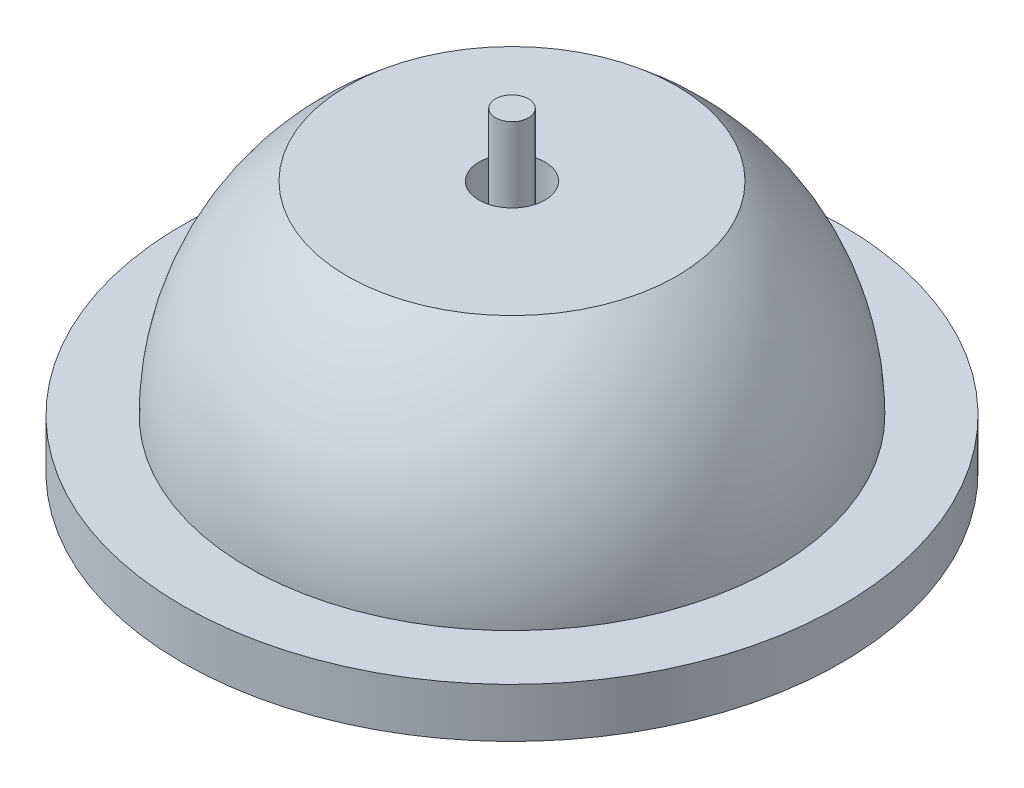
SolidWorks part; units mm, degrees
ref_plane "Front Plane" through (0, 0, 0) normal (0, 0, 1) x (1, 0, 0)
ref_plane "Top Plane" through (0, 0, 0) normal (0, 1, 0) x (1, 0, 0)
ref_plane "Right Plane" through (0, 0, 0) normal (1, 0, 0) x (0, 0, -1)
sketch "Sketch1" plane through (0, 0, 0) normal (0, 0, 1) x (1, 0, 0)
  line L0 (0, -54.4301) -> (0, 93.2078) construction
  line L1 (0, -64.8939) -> (0, 64.8939) construction
  line L2 (0, 0) -> (-100, 0)
  line L3 (-100, 0) -> (-100, 15)
  line L4 (-100, 15) -> (-80, 15)
  line L5 (-50, 76.5636) -> (0, 76.5636)
  line L6 (0, 76.5636) -> (0, 0)
  arc A0 (-80, 15) -> (-50, 76.5636) centre (-1.8321, 15) cw
revolve "Revolve1" add sketch "Sketch1" angle 360 about L0
sketch "Sketch5" plane through (0, 0, 0) normal (0, 0, 1) x (1, 0, 0)
  line L0 (0, -4.6123) -> (0, 80.659) construction
  line L1 (0, -64.8939) -> (0, 64.8939) construction
  line L2 (0, 80.659) -> (0, -4.6123)
  line L3 (0, -4.6123) -> (-10, -4.6123)
  line L4 (-10, -4.6123) -> (-10, 80.659)
  line L5 (-10, 80.659) -> (0, 80.659)
  dimension "D1" = 10
revolve "Cut-Revolve3" cut sketch "Sketch5" angle 360 about L0
ref_axis "Axis3" through (0, -28.2037, 0) along (0, 1, 0)
sketch "Sketch6" plane through (0, 0, 0) normal (0, 0, 1) x (1, 0, 0)
  line L0 (0, 95.6847) -> (-4.9974, 95.6847)
  line L1 (0, -64.8939) -> (0, 64.8939) construction
  line L2 (0, -28.2037) -> (0, 101.5841) construction
  line L3 (-4.9974, 95.6847) -> (-4.9974, -4.1791)
  line L4 (-4.9974, -4.1791) -> (0, -4.1791)
  line L5 (0, -4.1791) -> (0, 95.6847)
  dimension "D1" = 99.8638
  dimension "D2" = 99.8638
revolve "Revolve5" add sketch "Sketch6" angle 360 about L5
sketch "Sketch7" plane through (0, 0, 0) normal (0, 0, 1) x (1, 0, 0)
  line L0 (0, -4.1791) -> (-15.6433, -4.1791)
  line L1 (-4.9974, -4.1791) -> (4.9974, -4.1791) construction
  line L2 (0, -19.7299) -> (0, -4.1791)
  line L3 (-15.6433, -4.1791) -> (0, -19.7299) construction
  line L4 (0, -19.7299) -> (-13.0661, -24.8785) construction
  line L5 (-13.0661, -24.8785) -> (0, -19.7299) construction
  spline S0 degree 3 poles (-15.6433, -4.1791) (0, -19.7299) (-13.0661, -24.8785) (0, -19.7299) knots 0 0 0 0 1 1 1 1
  point P7 (0, 0)
  point P9 (0, -18.9922)
revolve "Revolve7" add sketch "Sketch7" angle 360 about axis through (0, -28.2037, 0) along (0, 1, 0)
sketch "Sketch8" plane through (0, 0, 0) normal (0, 0, 1) x (1, 0, 0)
  line L0 (72.1009, 49.242) -> (51.4251, 39.1667)
  line L1 (51.4251, 39.1667) -> (51.4251, 34.1667)
  line L2 (51.4251, 34.1667) -> (26.2096, 34.1667)
  line L3 (26.2096, 34.1667) -> (26.2096, 31.0304)
  line L4 (26.2096, 31.0304) -> (51.4251, 31.0304)
  line L5 (51.4251, 31.0304) -> (51.4251, 34.1667)
  line L6 (51.4251, 31.0304) -> (53.3272, 29.4754)
  line L7 (53.3272, 29.4754) -> (51.4251, 28.5485)
  line L8 (51.4251, 28.5485) -> (53.3272, 26.9935)
  line L9 (53.3272, 26.9935) -> (51.4251, 26.0666)
  line L10 (51.4251, 26.0666) -> (53.3272, 24.5116)
  line L11 (53.3272, 24.5116) -> (51.4251, 23.5847)
  line L12 (51.4251, 23.5847) -> (53.3272, 22.0297)
  line L13 (53.3272, 22.0297) -> (51.4251, 21.1027)
  line L14 (51.4251, 21.1027) -> (53.3272, 19.5477)
  line L15 (53.3272, 19.5477) -> (51.4251, 18.6208)
  line L16 (51.4251, 18.6208) -> (53.3272, 17.0658)
  line L17 (53.3272, 17.0658) -> (51.4251, 16.1389)
  line L18 (51.4251, 16.1389) -> (52.8182, 15)
  line L19 (100, 15) -> (-100, 15) construction
  line L20 (52.8182, 15) -> (49.7885, 15)
  line L21 (49.7885, 15) -> (35.9878, 19.7191) construction
  line L22 (35.9878, 19.7191) -> (16.4037, 19.2263) construction
  line L23 (16.4037, 19.2263) -> (16.4037, 15) construction
  line L24 (16.4037, 15) -> (49.7885, 15)
  arc A0 (80, 15) -> (50, 76.5636) centre (1.8321, 15) ccw construction
  spline S0 degree 3 poles (49.7885, 15) (35.9878, 19.7191) (16.4037, 19.2263) (16.4037, 15) knots 0 0 0 0 1 1 1 1
revolve "Cut-Revolve5" cut sketch "Sketch8" angle 360 about axis through (0, -28.2037, 0) along (0, 1, 0)
